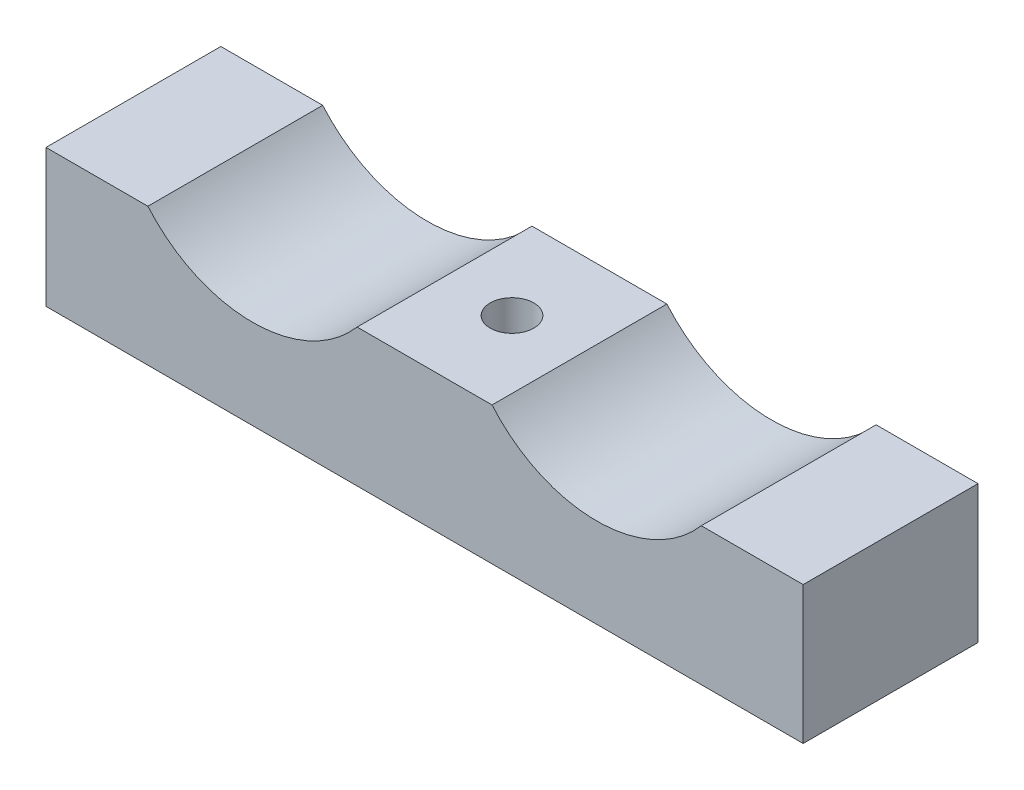
SolidWorks part; units mm, degrees
ref_plane "Front Plane" through (0, 0, 0) normal (0, 0, 1) x (1, 0, 0)
ref_plane "Top Plane" through (0, 0, 0) normal (0, 1, 0) x (1, 0, 0)
ref_plane "Right Plane" through (0, 0, 0) normal (1, 0, 0) x (0, 0, -1)
sketch "Sketch4" plane through (0, 0, 0) normal (0, 0, 1) x (1, 0, 0)
  line L1 (0, 0) -> (55, 0)
  line L2 (0, 0) -> (0, 10)
  line L3 (0, 10) -> (55, 10)
  line L4 (55, 0) -> (55, 10)
  dimension "D1" = 10
  dimension "D2" = 55
extrude "Boss-Extrude1" add sketch "Sketch4" along normal blind 12.7
sketch "Sketch5" plane through (0, 0, 12.7) normal (0, 0, 1) x (1, 0, 0)
  line L0 (0, 10) -> (0, 0) construction
  line L2 (0, 0) -> (55, 0) construction
  circle A0 centre (15, 16.5) radius 10
  circle A1 centre (40, 16.5) radius 10
  dimension "D3" = 20
  dimension "D1" = 25
  dimension "D2" = 15
  dimension "D4" = 16.5
extrude "Cut-Extrude1" cut sketch "Sketch5" against normal through all
sketch "Sketch8" plane through (0, 10, 0) normal (0, 1, 0) x (1, 0, 0)
  line L0 (22.5993, 0) -> (22.5993, -12.7) construction
  line L1 (32.4007, 0) -> (22.5993, 0) construction
  circle A0 centre (27.5, -6.35) radius 1.5875
  point P5 (22.5993, -6.35)
  point P9 (27.5, 0)
  dimension "D1" = 3.175
extrude "Cut-Extrude3" cut sketch "Sketch8" against normal through all
